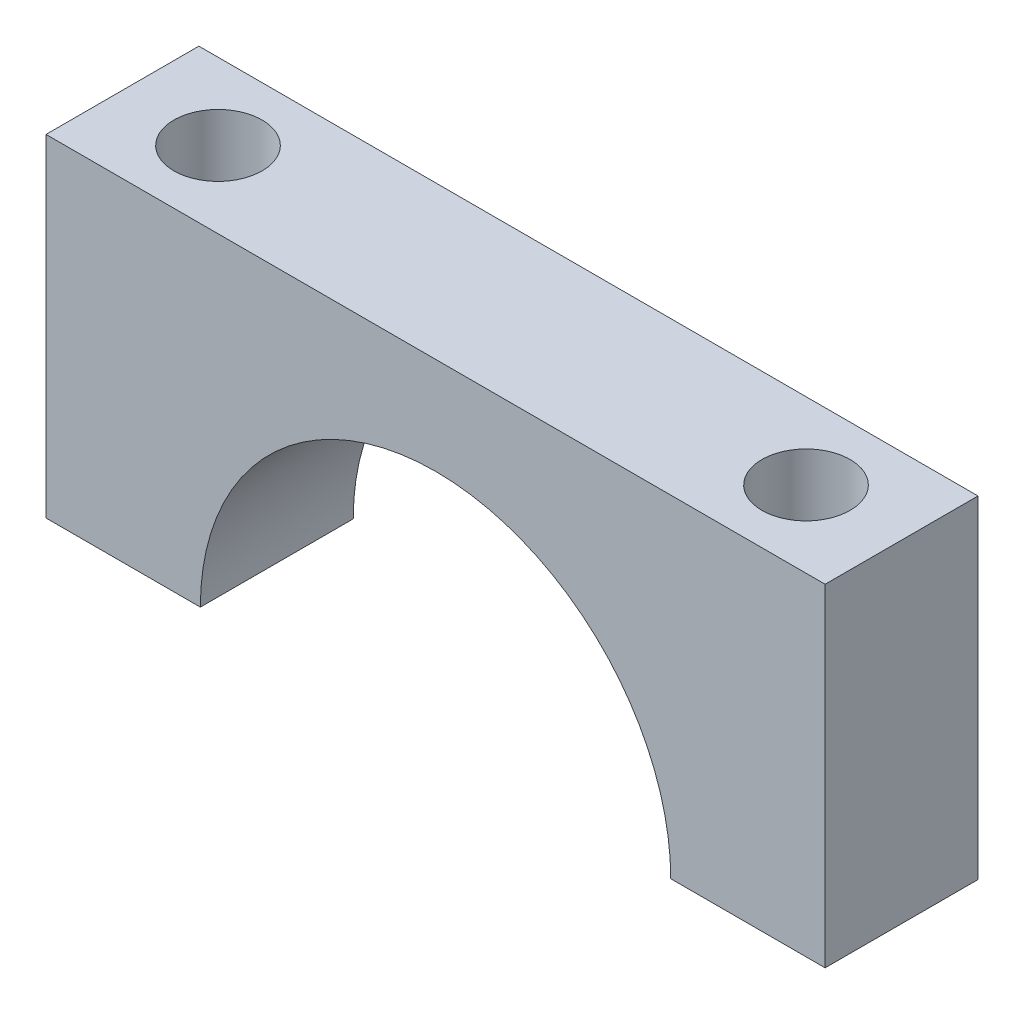
SolidWorks part; units mm, degrees
ref_plane "Front Plane" through (0, 0, 0) normal (0, 0, 1) x (1, 0, 0)
ref_plane "Top Plane" through (0, 0, 0) normal (0, 1, 0) x (1, 0, 0)
ref_plane "Right Plane" through (0, 0, 0) normal (1, 0, 0) x (0, 0, -1)
sketch "Sketch1" plane through (0, 0, 0) normal (0, 0, 1) x (1, 0, 0)
  line L0 (8, 0) -> (13.25, 0)
  line L1 (13.25, 0) -> (13.25, 11.3)
  line L2 (13.25, 11.3) -> (-13.25, 11.3)
  line L3 (-13.25, 11.3) -> (-13.25, 0)
  line L4 (-13.25, 0) -> (-8, 0)
  arc A0 (8, 0) -> (-8, 0) centre (0, 0) ccw
  point P5 (0, 11.3)
  dimension "D3" = 16
  dimension "D1" = 26.5
  dimension "D2" = 11.3
extrude "Boss-Extrude1" add sketch "Sketch1" along normal mid plane 5.2
sketch "Sketch2" plane through (0, 11.3, 0) normal (0, 1, 0) x (1, 0, 0)
  line L0 (10, 0) -> (-10, 0) construction
  circle A0 centre (-10, 0) radius 1.5
  circle A1 centre (10, 0) radius 1.5
  point P4 (0, 0)
  dimension "D1" = 3
  dimension "D2" = 20
extrude "Cut-Extrude1" cut sketch "Sketch2" against normal through all
